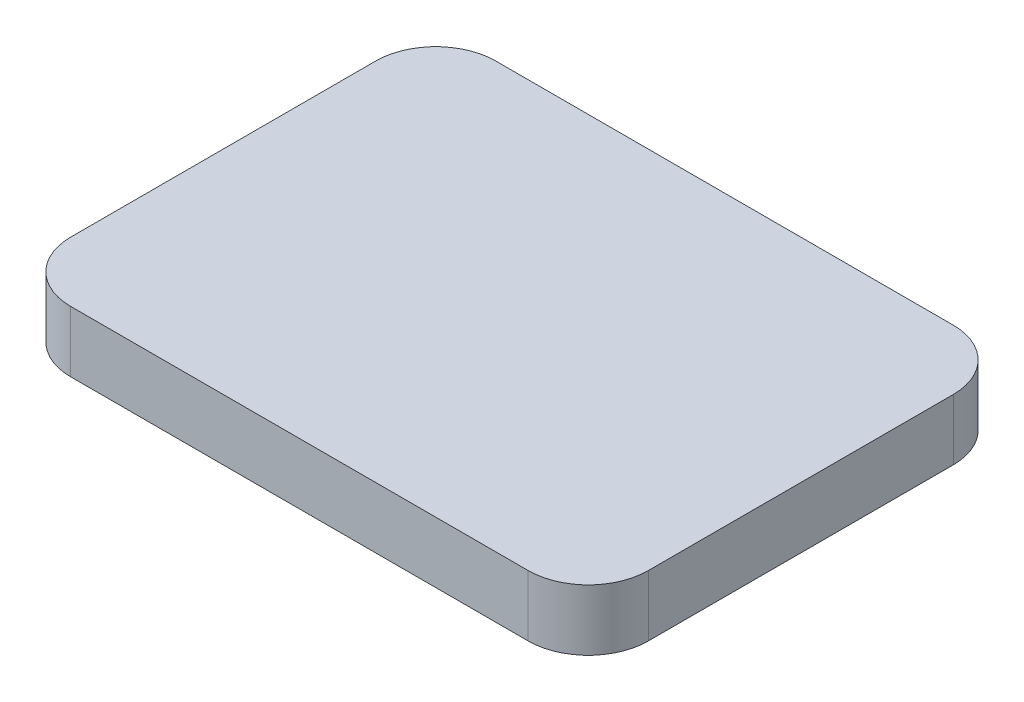
SolidWorks part; units mm, degrees
ref_plane "Front Plane" through (0, 0, 0) normal (0, 0, 1) x (1, 0, 0)
ref_plane "Top Plane" through (0, 0, 0) normal (0, 1, 0) x (1, 0, 0)
ref_plane "Right Plane" through (0, 0, 0) normal (1, 0, 0) x (0, 0, -1)
sketch "Sketch1" plane through (0, 0, 0) normal (0, 1, 0) x (1, 0, 0)
  line L1 (-38.1, -35.4) -> (38.1, -35.4)
  line L2 (-48.1, -25.4) -> (-48.1, 25.4)
  line L3 (-38.1, 35.4) -> (38.1, 35.4)
  line L4 (48.1, -25.4) -> (48.1, 25.4)
  line L5 (-48.1, -35.4) -> (48.1, 35.4) construction
  line L6 (-48.1, 35.4) -> (48.1, -35.4) construction
  arc A0 (-48.1, 25.4) -> (-38.1, 35.4) centre (-38.1, 25.4) cw
  arc A1 (-38.1, -35.4) -> (-48.1, -25.4) centre (-38.1, -25.4) cw
  arc A2 (38.1, -35.4) -> (48.1, -25.4) centre (38.1, -25.4) ccw
  arc A3 (38.1, 35.4) -> (48.1, 25.4) centre (38.1, 25.4) cw
  point P0 (0, 0)
  dimension "D1" = 10
extrude "Boss-Extrude1" add sketch "Sketch1" along normal blind 10.16
